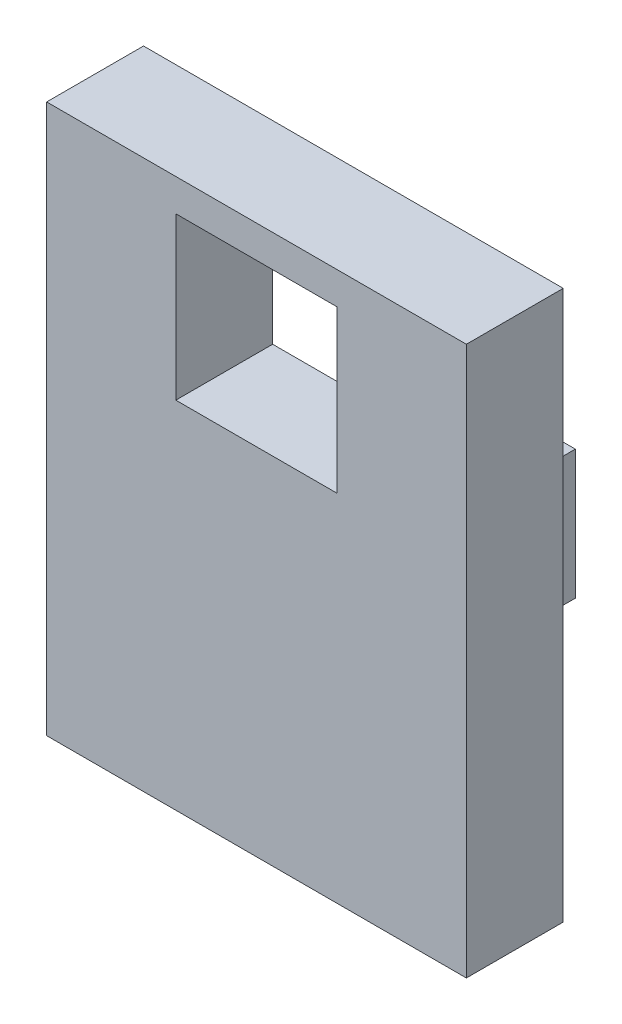
SolidWorks part; units mm, degrees
ref_plane "Front Plane" through (0, 0, 0) normal (0, 0, 1) x (1, 0, 0)
ref_plane "Top Plane" through (0, 0, 0) normal (0, 1, 0) x (1, 0, 0)
ref_plane "Right Plane" through (0, 0, 0) normal (1, 0, 0) x (0, 0, -1)
sketch "Sketch1" plane through (0, 0, 0) normal (0, 0, 1) x (1, 0, 0)
  line L1 (13.694, 16.8692) -> (-27.581, 16.8692)
  line L2 (13.694, 16.8692) -> (13.694, -37.1058)
  line L3 (13.694, -37.1058) -> (-27.581, -37.1058)
  line L4 (-27.581, 16.8692) -> (-27.581, -37.1058)
  line L5 (-14.881, 13.6942) -> (0.994, 13.6942)
  line L6 (-14.881, 13.6942) -> (-14.881, -2.1808)
  line L7 (-14.881, -2.1808) -> (0.994, -2.1808)
  line L8 (0.994, 13.6942) -> (0.994, -2.1808)
  dimension "D1" = 3.175
  dimension "D2" = 12.7
  dimension "D3" = 15.875
  dimension "D4" = 12.7
  dimension "D5" = 15.875
  dimension "D6" = 53.975
extrude "Boss-Extrude1" add sketch "Sketch1" against normal blind 9.525
sketch "Sketch2" plane through (0, 0, -9.525) normal (0, 0, -1) x (-1, 0, 0)
  line L1 (0.5935, -24.4058) -> (13.2935, -24.4058)
  line L2 (0.5935, -24.4058) -> (0.5935, -11.7058)
  line L3 (0.5935, -11.7058) -> (13.2935, -11.7058)
  line L4 (13.2935, -24.4058) -> (13.2935, -11.7058)
  line L5 (27.581, -37.1058) -> (-13.694, -37.1058) construction
  line L6 (6.9435, -11.7058) -> (6.9435, -24.4058) construction
  point P8 (6.9435, -37.1058)
  dimension "D1" = 12.7
  dimension "D2" = 12.7
  dimension "D3" = 12.7
extrude "Boss-Extrude2" add sketch "Sketch2" along normal up to surface (15.4771 mm away)
